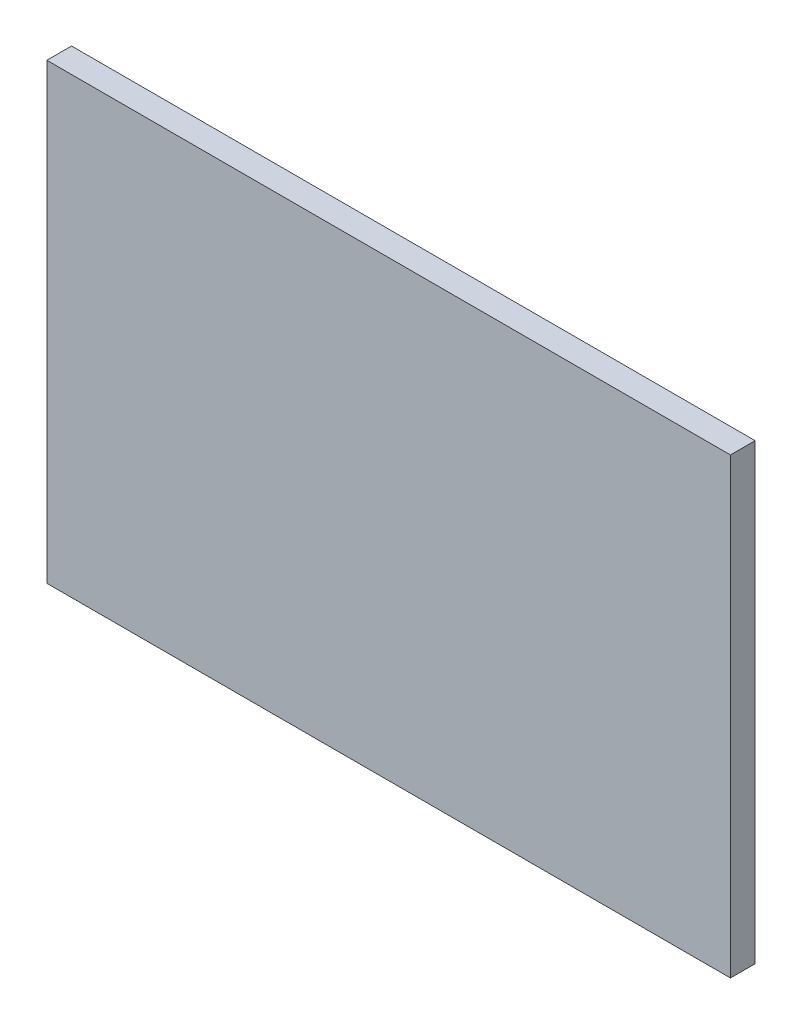
SolidWorks part; units mm, degrees
ref_plane "Plan de face" through (0, 0, 0) normal (0, 0, 1) x (1, 0, 0)
ref_plane "Plan de dessus" through (0, 0, 0) normal (0, 1, 0) x (1, 0, 0)
ref_plane "Plan de droite" through (0, 0, 0) normal (1, 0, 0) x (0, 0, -1)
sketch "Esquisse1" plane through (0, 0, 0) normal (0, 0, 1) x (1, 0, 0)
  line L1 (0, 0) -> (83, 0)
  line L2 (0, 0) -> (0, 55)
  line L3 (0, 55) -> (83, 55)
  line L4 (83, 0) -> (83, 55)
  dimension "D1" = 83
  dimension "D2" = 55
extrude "Boss.-Extru.1" add sketch "Esquisse1" along normal blind 3
sketch "Esquisse2" plane through (0, 0, 3) normal (0, 0, 1) x (1, 0, 0)
  line L0 (0, 0) -> (83, 0) construction
  line L1 (0, 55) -> (5, 55)
  line L2 (0, 55) -> (0, 0)
  line L3 (0, 0) -> (5, 0)
  line L4 (5, 55) -> (5, 0)
  text T0 "-  EHAO    405585\r\n\r\n+ 3.7V 3000mAh" font "Consolas" height in points 8
  dimension "D1" = 5
